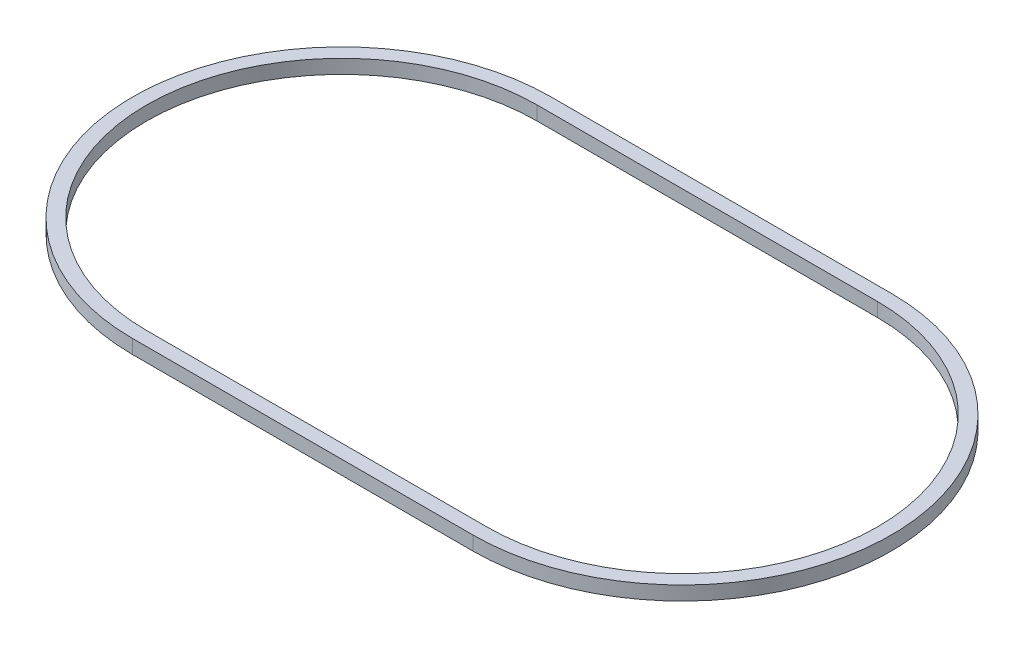
SolidWorks part; units mm, degrees
material "BUTYL"
ref_plane "Ön Düzlem" through (0, 0, 0) normal (0, 0, 1) x (1, 0, 0)
ref_plane "Üst Düzlem" through (0, 0, 0) normal (0, 1, 0) x (1, 0, 0)
ref_plane "Sağ Düzlem" through (0, 0, 0) normal (1, 0, 0) x (0, 0, -1)
sketch "Sketch1" plane through (0, 0, 0) normal (0, 1, 0) x (1, 0, 0)
  line L0 (0, 0) -> (61, 0) construction
  line L1 (0, 35) -> (61, 35)
  line L2 (0, -35) -> (61, -35)
  line L3 (0, 0) -> (61, 0) construction
  line L4 (0, 37.5) -> (61, 37.5)
  line L5 (0, -37.5) -> (61, -37.5)
  arc A0 (0, 35) -> (0, -35) centre (0, 0) ccw
  arc A1 (61, -35) -> (61, 35) centre (61, 0) ccw
  arc A2 (0, 37.5) -> (0, -37.5) centre (0, 0) ccw
  arc A3 (61, -37.5) -> (61, 37.5) centre (61, 0) ccw
  point P3 (30.5, 0)
  point P10 (30.5, 0)
  dimension "D1" = 70
  dimension "D2" = 61
  dimension "D3" = 75
  dimension "D4" = 61
extrude "Boss-Extrude1" add sketch "Sketch1" along normal blind 2.5
